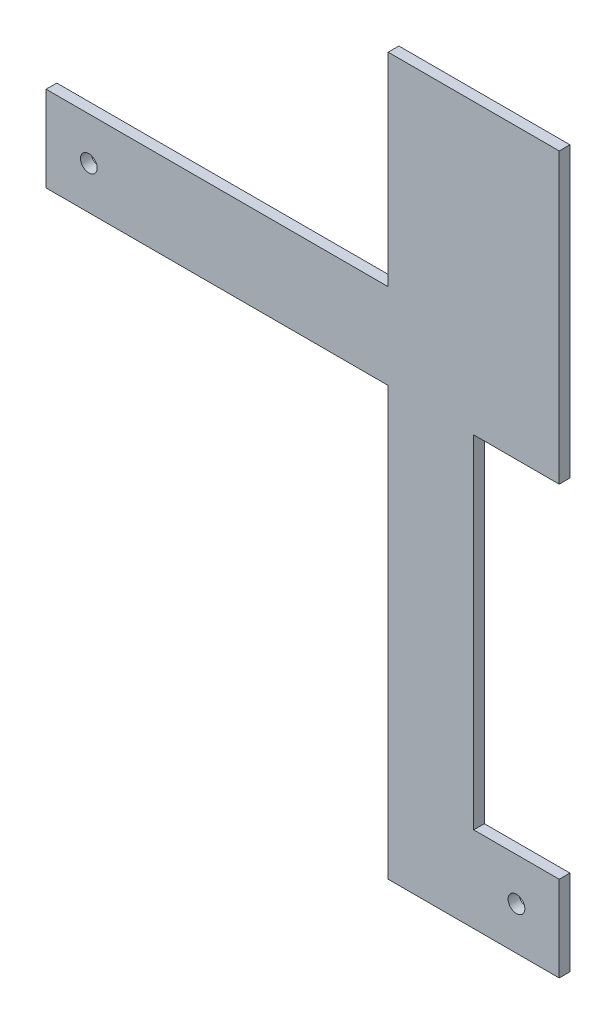
SolidWorks part; units mm, degrees
ref_plane "Front Plane" through (0, 0, 0) normal (1, 0, 0) x (0, 1, 0)
ref_plane "Top Plane" through (0, 0, 0) normal (0, 0, 1) x (0, 1, 0)
ref_plane "Right Plane" through (0, 0, 0) normal (0, 1, 0) x (-1, 0, 0)
sketch "Sketch1" plane through (0, 0, 0) normal (0, 0, 1) x (0, 1, 0)
  line L1 (-106.3625, -12.7) -> (106.3625, -12.7) construction
  line L2 (-106.3625, -12.7) -> (-106.3625, 12.7) construction
  line L3 (-106.3625, 12.7) -> (106.3625, 12.7) construction
  line L4 (106.3625, -12.7) -> (106.3625, 12.7) construction
  line L5 (-106.3625, -12.7) -> (106.3625, 12.7) construction
  line L6 (-106.3625, 12.7) -> (106.3625, -12.7) construction
  line L7 (-106.3625, -12.7) -> (-80.9625, -12.7) construction
  line L8 (-106.3625, -12.7) -> (-106.3625, -38.1) construction
  line L9 (-106.3625, -38.1) -> (-80.9625, -38.1) construction
  line L10 (-80.9625, -12.7) -> (-80.9625, -38.1) construction
  line L13 (-80.9625, -12.7) -> (-80.9625, -38.1)
  line L14 (-80.9625, -38.1) -> (-106.3625, -38.1)
  line L15 (-106.3625, -38.1) -> (-106.3625, 12.7)
  line L17 (20.6375, 12.7) -> (46.0375, 12.7) construction
  line L18 (20.6375, 12.7) -> (20.6375, 114.3) construction
  line L19 (20.6375, 114.3) -> (46.0375, 114.3) construction
  line L20 (46.0375, 12.7) -> (46.0375, 114.3) construction
  line L21 (46.0375, 12.7) -> (46.0375, 114.3)
  line L22 (46.0375, 114.3) -> (20.6375, 114.3)
  line L23 (20.6375, 114.3) -> (20.6375, 12.7)
  line L24 (20.6375, 12.7) -> (-106.3625, 12.7)
  line L25 (-80.9625, -12.7) -> (20.6375, -12.7)
  line L26 (20.6375, -12.7) -> (106.3625, -12.7) construction
  line L27 (20.6375, -12.7) -> (20.6375, -38.1) construction
  line L29 (106.3625, -12.7) -> (106.3625, -63.5) construction
  line L34 (20.6375, -12.7) -> (20.6375, -38.1)
  line L35 (20.6375, -38.1) -> (106.3625, -38.1)
  line L39 (106.3625, -38.1) -> (106.3625, 12.7)
  line L40 (106.3625, 12.7) -> (46.0375, 12.7)
  point P0 (0, 0)
  point P17 (20.6375, -25.4)
  dimension "D1" = 212.725
  dimension "D2" = 25.4
  dimension "D3" = 25.4
  dimension "D4" = 25.4
  dimension "D5" = 101.6
  dimension "D6" = 25.4
  dimension "D7" = 127
  dimension "D8" = 127
  dimension "D9" = 25.4
extrude "Boss-Extrude1" add sketch "Sketch1" along normal blind 3.175
sketch "Sketch2" plane through (0, 0, 3.175) normal (0, 0, 1) x (1, 0, 0)
  line L0 (38.1, -106.3625) -> (38.1, -80.9625) construction
  line L1 (-12.7, -106.3625) -> (38.1, -106.3625) construction
  line L2 (-114.3, 46.0375) -> (-114.3, 20.6375) construction
  line L3 (-114.3, 20.6375) -> (-12.7, 20.6375) construction
  point P0 (25.4, -93.6625)
  point P1 (-153.252, -35.1554)
  point P6 (-101.6, 33.3375)
  point P8 (-174.4616, 15.3753)
  dimension "D1" = 12.7
  dimension "D2" = 12.7
  dimension "D3" = 12.7
  dimension "D4" = 12.7
hole_wizard "#9 (0.196) Diameter Hole1" positions "Sketch2" profile "Sketch3" hole size "#9" standard "ANSI Inch" end condition through all
sketch "Sketch3" plane through (25.4, -93.6625, 3.175) normal (1, 0, 0) x (0, -1, 0)
  line L0 (0, 0) -> (0, 3.175)
  line L1 (0, 3.175) -> (2.4892, 3.175)
  line L2 (2.4892, 3.175) -> (2.4892, 0)
  line L5 (2.4892, 0) -> (0, 0)
  line L11 (0, -6.35) -> (0, 107.95) construction
  dimension "Thru Hole Dia." = 4.9784
  dimension "Thru Hole Depth" = 3.175
